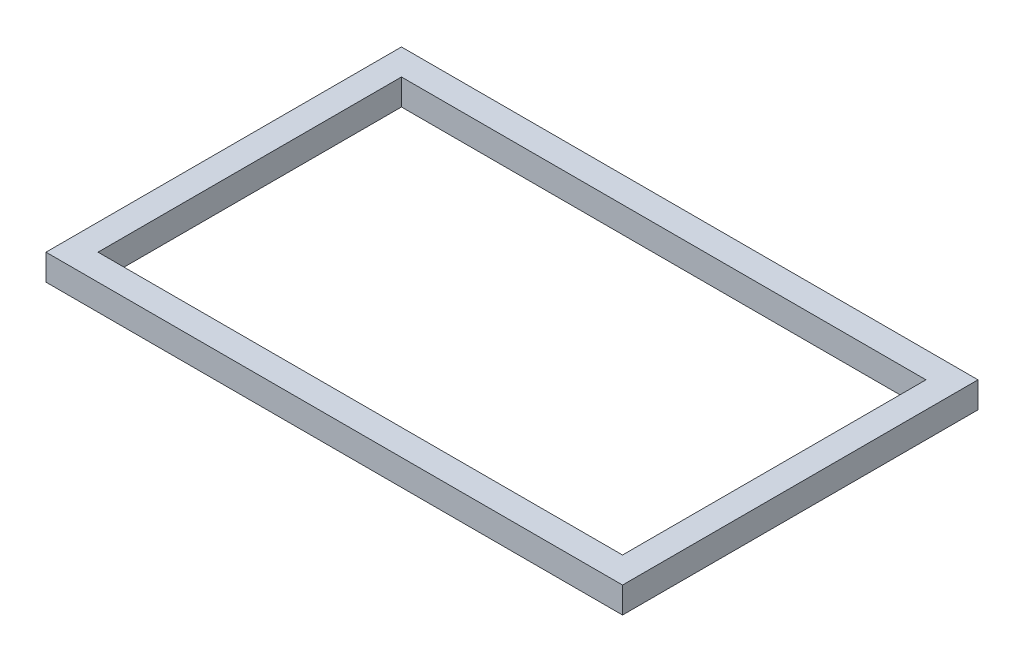
SolidWorks part; units mm, degrees
ref_plane "Front Plane" through (0, 0, 0) normal (0, 0, 1) x (1, 0, 0)
ref_plane "Top Plane" through (0, 0, 0) normal (0, 1, 0) x (1, 0, 0)
ref_plane "Right Plane" through (0, 0, 0) normal (1, 0, 0) x (0, 0, -1)
sketch "Sketch1" plane through (0, 0, 0) normal (0, 1, 0) x (1, 0, 0)
  line L0 (-131.4268, 80.2959) -> (-131.4268, -129.7041)
  line L1 (-149.4268, 98.2959) -> (249.5732, 98.2959)
  line L2 (-149.4268, 98.2959) -> (-149.4268, -147.7041)
  line L3 (-149.4268, -147.7041) -> (249.5732, -147.7041)
  line L4 (249.5732, 98.2959) -> (249.5732, -147.7041)
  line L7 (-131.4268, -129.7041) -> (231.5732, -129.7041)
  line L8 (231.5732, 80.2959) -> (231.5732, -129.7041)
  line L9 (-131.4268, 80.2959) -> (231.5732, 80.2959)
  point P4 (50.0732, -24.7041)
  dimension "D1" = 399
  dimension "D2" = 246
  dimension "D3" = 18
extrude "Boss-Extrude1" add sketch "Sketch1" along normal blind 18
